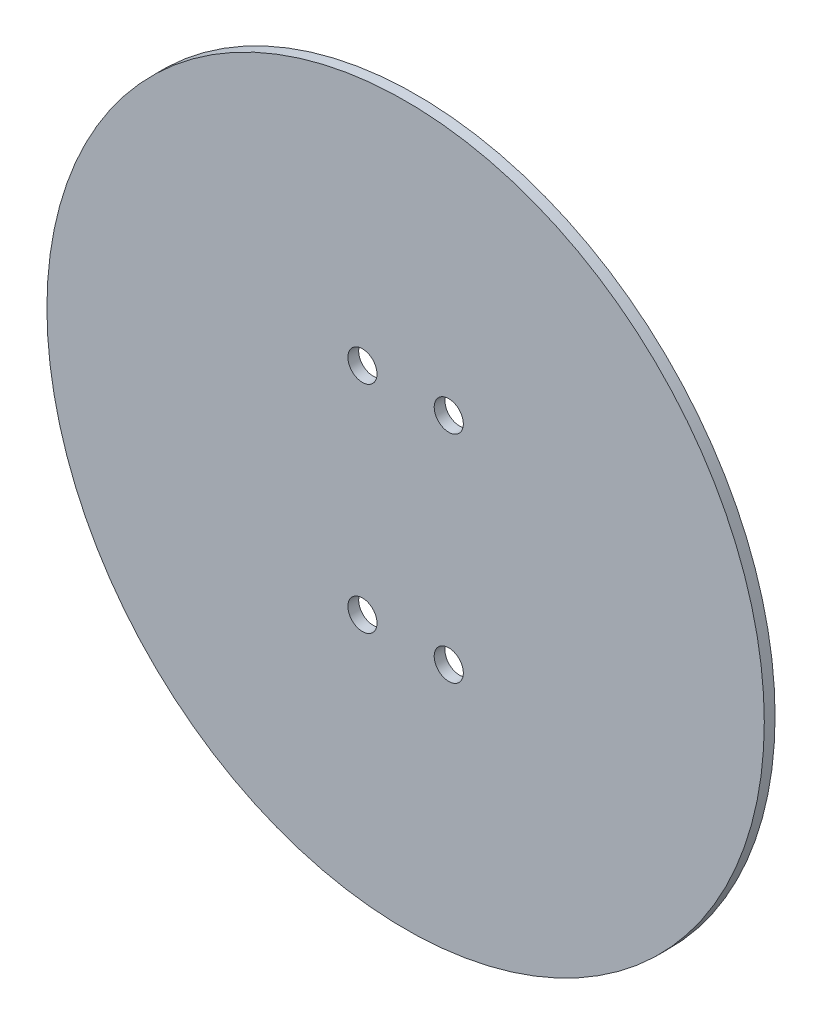
SolidWorks part; units mm, degrees
ref_plane "Front Plane" through (0, 0, 0) normal (0, 0, 1) x (1, 0, 0)
ref_plane "Top Plane" through (0, 0, 0) normal (0, 1, 0) x (1, 0, 0)
ref_plane "Right Plane" through (0, 0, 0) normal (1, 0, 0) x (0, 0, -1)
sketch "Sketch1" plane through (0, 0, 0) normal (0, 0, 1) x (1, 0, 0)
  circle A0 centre (0, 0) radius 84.455
  dimension "D1" = 168.91
extrude "Boss-Extrude1" add sketch "Sketch1" along normal blind 2.54
sketch "Sketch2" plane through (0, 0, 2.54) normal (0, 0, 1) x (1, 0, 0)
  line L0 (0, 0) -> (60.2509, 0) construction
  line L1 (0, 0) -> (0, 49.4395) construction
  circle A0 centre (0, 0) radius 12.7 construction
  circle A1 centre (-10.16, 25.4) radius 3.429
  circle A2 centre (10.16, 25.4) radius 3.429
  circle A3 centre (10.16, -25.4) radius 3.429
  circle A4 centre (-10.16, -25.4) radius 3.429
  dimension "D1" = 25.4
  dimension "D2" = 6.858
  dimension "D3" = 25.4
  dimension "D4" = 10.16
extrude "Cut-Extrude1" cut sketch "Sketch2" against normal blind 2.54
